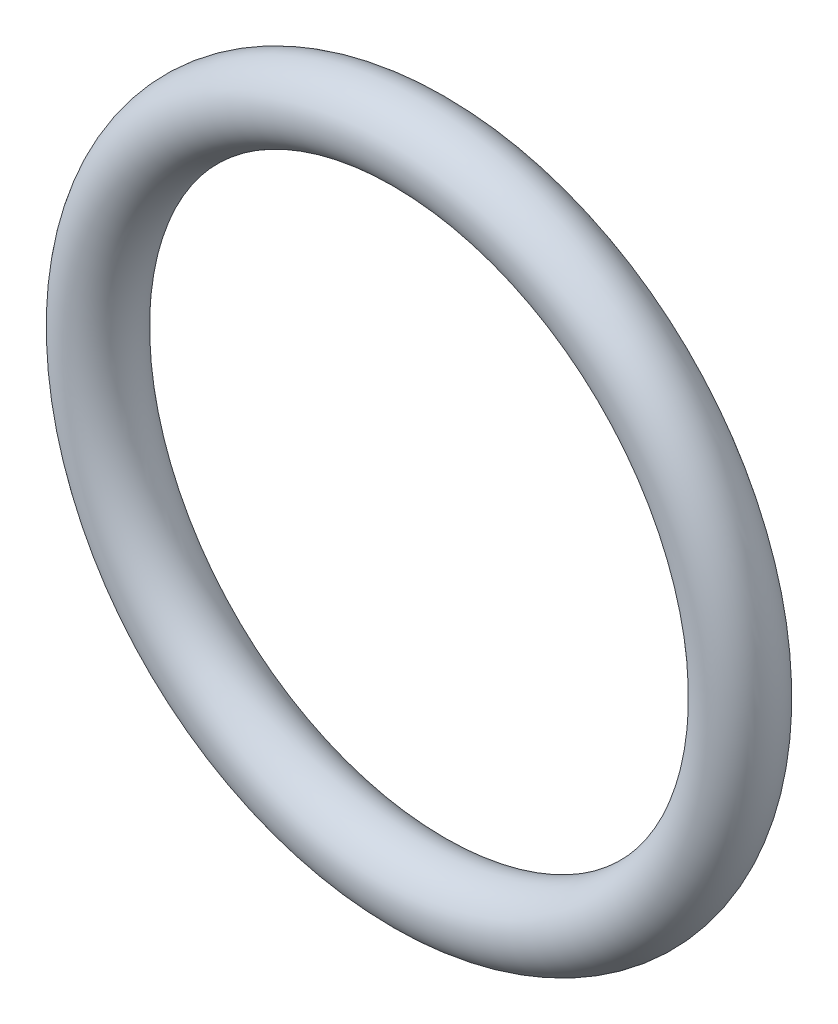
SolidWorks part; units mm, degrees
ref_plane "Front Plane" through (0, 0, 0) normal (0, 0, 1) x (1, 0, 0)
ref_plane "Top Plane" through (0, 0, 0) normal (0, 1, 0) x (1, 0, 0)
ref_plane "Right Plane" through (0, 0, 0) normal (1, 0, 0) x (0, 0, -1)
sketch "Sketch1" plane through (0, 0, 0) normal (0, 0, 1) x (1, 0, 0)
  line L0 (0, -9.5885) -> (0, -12.0523)
  circle A0 centre (0, 0) radius 9.5885
  circle A1 centre (0, 0) radius 12.0523
  circle A2 centre (0, 0) radius 10.8204 construction
  circle A3 centre (0, 0) radius 7.9375 construction
  point P6 (0, -10.8204)
  dimension "OD" = 24.1046
  dimension "ID" = 19.177
  dimension "For Tube OD" = 15.875
sketch "Sketch2" plane through (0, 0, 0) normal (1, 0, 0) x (0, 0, -1)
  circle A0 centre (0, -10.8204) radius 1.2319
  dimension "Width" = 2.4638
sketch "Sketch3" plane through (0, 0, 0) normal (1, 0, 0) x (0, 0, -1)
  circle A0 centre (0, -10.8204) radius 1.2319 construction
  circle A1 centre (0, -10.8204) radius 1.2319
sketch "Sketch4" plane through (0, 0, 0) normal (0, 0, 1) x (1, 0, 0)
  circle A0 centre (0, 0) radius 10.8204 construction
  circle A1 centre (0, 0) radius 10.8204
sweep "Sweep1" add profiles "Sketch3" path "Sketch4"
